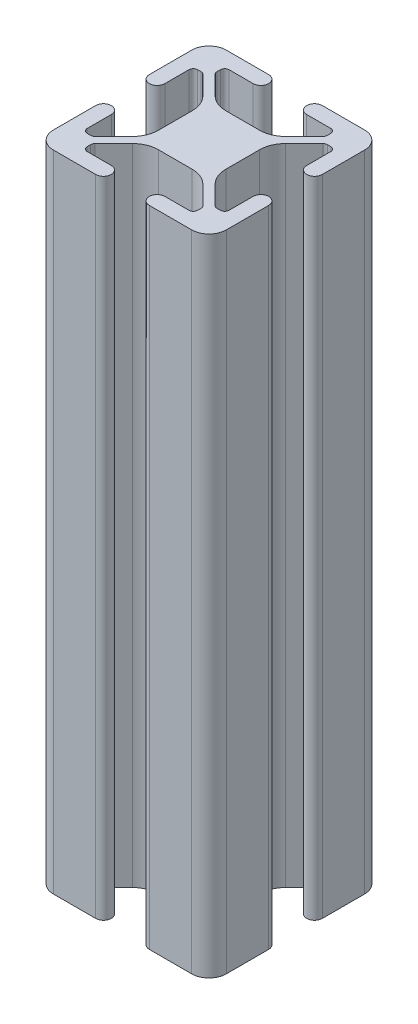
SolidWorks part; units mm, degrees
ref_plane "前视基准面" through (0, 0, 0) normal (0, 0, 1) x (1, 0, 0)
ref_plane "上视基准面" through (0, 0, 0) normal (0, 1, 0) x (1, 0, 0)
ref_plane "右视基准面" through (0, 0, 0) normal (1, 0, 0) x (0, 0, -1)
sketch "草图1" plane through (0, 0, 0) normal (0, 1, 0) x (1, 0, 0)
  line L0 (-1.0428, -10.0859) -> (3.8572, -10.0859)
  line L1 (1.0762, -11.8859) -> (3.8572, -11.8859)
  line L2 (2.8854, -15.3072) -> (0.7226, -13.1443)
  line L3 (2.1786, -16.0141) -> (0.0157, -13.8512)
  line L4 (-3.0428, -12.0859) -> (-3.0428, -16.9859)
  line L5 (-1.2428, -14.2048) -> (-1.2428, -16.9859)
  line L6 (-0.7428, -13.7048) -> (-0.3378, -13.7048)
  line L7 (0.5762, -12.3859) -> (0.5762, -12.7908)
  line L8 (-1.0428, -30.0859) -> (3.8572, -30.0859)
  line L9 (1.0762, -28.2859) -> (3.8572, -28.2859)
  line L10 (2.8854, -24.8645) -> (0.7226, -27.0274)
  line L11 (2.1786, -24.1577) -> (0.0157, -26.3205)
  line L12 (-3.0428, -28.0859) -> (-3.0428, -23.1859)
  line L13 (-1.2428, -25.9669) -> (-1.2428, -23.1859)
  line L14 (-0.7428, -26.4669) -> (-0.3378, -26.4669)
  line L15 (0.5762, -27.7859) -> (0.5762, -27.3809)
  line L16 (14.9572, -10.0859) -> (10.0572, -10.0859)
  line L17 (12.8383, -11.8859) -> (10.0572, -11.8859)
  line L18 (11.029, -15.3072) -> (13.1919, -13.1443)
  line L19 (11.7359, -16.0141) -> (13.8988, -13.8512)
  line L20 (16.9572, -12.0859) -> (16.9572, -16.9859)
  line L21 (15.1572, -14.2048) -> (15.1572, -16.9859)
  line L22 (14.6572, -13.7048) -> (14.2523, -13.7048)
  line L23 (13.3383, -12.3859) -> (13.3383, -12.7908)
  line L24 (14.9572, -30.0859) -> (10.0572, -30.0859)
  line L25 (12.8383, -28.2859) -> (10.0572, -28.2859)
  line L26 (11.029, -24.8645) -> (13.1919, -27.0274)
  line L27 (11.7359, -24.1577) -> (13.8988, -26.3205)
  line L28 (16.9572, -28.0859) -> (16.9572, -23.1859)
  line L29 (15.1572, -25.9669) -> (15.1572, -23.1859)
  line L30 (14.6572, -26.4669) -> (14.2523, -26.4669)
  line L31 (13.3383, -27.7859) -> (13.3383, -27.3809)
  line L32 (5.0068, -16.1859) -> (8.9077, -16.1859)
  line L33 (10.8572, -18.1354) -> (10.8572, -22.0363)
  line L34 (3.0572, -18.1354) -> (3.0572, -22.0363)
  line L35 (5.0068, -23.9859) -> (8.9077, -23.9859)
  circle A0 centre (6.9572, -20.0859) radius 2.5
  arc A1 (2.8854, -15.3072) -> (5.0068, -16.1859) centre (5.0068, -13.1859) ccw
  arc A2 (3.0572, -18.1354) -> (2.1786, -16.0141) centre (0.0572, -18.1354) ccw
  arc A3 (3.8572, -11.8859) -> (3.8572, -10.0859) centre (3.8572, -10.9859) ccw
  arc A4 (0.5762, -12.7908) -> (0.7226, -13.1443) centre (1.0762, -12.7908) ccw
  arc A5 (0.0157, -13.8512) -> (-0.3378, -13.7048) centre (-0.3378, -14.2048) ccw
  arc A6 (-3.0428, -16.9859) -> (-1.2428, -16.9859) centre (-2.1428, -16.9859) ccw
  arc A7 (-1.0428, -10.0859) -> (-3.0428, -12.0859) centre (-1.0428, -12.0859) ccw
  arc A8 (-0.7428, -13.7048) -> (-1.2428, -14.2048) centre (-0.7428, -14.2048) ccw
  arc A9 (1.0762, -11.8859) -> (0.5762, -12.3859) centre (1.0762, -12.3859) ccw
  arc A10 (5.0068, -23.9859) -> (2.8854, -24.8645) centre (5.0068, -26.9859) ccw
  arc A11 (2.1786, -24.1577) -> (3.0572, -22.0363) centre (0.0572, -22.0363) ccw
  arc A12 (3.8572, -30.0859) -> (3.8572, -28.2859) centre (3.8572, -29.1859) ccw
  arc A13 (0.7226, -27.0274) -> (0.5762, -27.3809) centre (1.0762, -27.3809) ccw
  arc A14 (-0.3378, -26.4669) -> (0.0157, -26.3205) centre (-0.3378, -25.9669) ccw
  arc A15 (-1.2428, -23.1859) -> (-3.0428, -23.1859) centre (-2.1428, -23.1859) ccw
  arc A16 (-3.0428, -28.0859) -> (-1.0428, -30.0859) centre (-1.0428, -28.0859) ccw
  arc A17 (-1.2428, -25.9669) -> (-0.7428, -26.4669) centre (-0.7428, -25.9669) ccw
  arc A18 (0.5762, -27.7859) -> (1.0762, -28.2859) centre (1.0762, -27.7859) ccw
  arc A19 (8.9077, -16.1859) -> (11.029, -15.3072) centre (8.9077, -13.1859) ccw
  arc A20 (11.7359, -16.0141) -> (10.8572, -18.1354) centre (13.8572, -18.1354) ccw
  arc A21 (10.0572, -10.0859) -> (10.0572, -11.8859) centre (10.0572, -10.9859) ccw
  arc A22 (13.1919, -13.1443) -> (13.3383, -12.7908) centre (12.8383, -12.7908) ccw
  arc A23 (14.2523, -13.7048) -> (13.8988, -13.8512) centre (14.2523, -14.2048) ccw
  arc A24 (15.1572, -16.9859) -> (16.9572, -16.9859) centre (16.0572, -16.9859) ccw
  arc A25 (16.9572, -12.0859) -> (14.9572, -10.0859) centre (14.9572, -12.0859) ccw
  arc A26 (15.1572, -14.2048) -> (14.6572, -13.7048) centre (14.6572, -14.2048) ccw
  arc A27 (13.3383, -12.3859) -> (12.8383, -11.8859) centre (12.8383, -12.3859) ccw
  arc A28 (11.029, -24.8645) -> (8.9077, -23.9859) centre (8.9077, -26.9859) ccw
  arc A29 (10.8572, -22.0363) -> (11.7359, -24.1577) centre (13.8572, -22.0363) ccw
  arc A30 (10.0572, -28.2859) -> (10.0572, -30.0859) centre (10.0572, -29.1859) ccw
  arc A31 (13.3383, -27.3809) -> (13.1919, -27.0274) centre (12.8383, -27.3809) ccw
  arc A32 (13.8988, -26.3205) -> (14.2523, -26.4669) centre (14.2523, -25.9669) ccw
  arc A33 (16.9572, -23.1859) -> (15.1572, -23.1859) centre (16.0572, -23.1859) ccw
  arc A34 (14.9572, -30.0859) -> (16.9572, -28.0859) centre (14.9572, -28.0859) ccw
  arc A35 (14.6572, -26.4669) -> (15.1572, -25.9669) centre (14.6572, -25.9669) ccw
  arc A36 (12.8383, -28.2859) -> (13.3383, -27.7859) centre (12.8383, -27.7859) ccw
  point P0 (0, 0.001)
  point P1 (0.001, 0.001)
  point P2 (0.001, 0)
extrude "凸台-拉伸1" add sketch "草图1" along normal blind 74.5 contours L5 A6 L4 A7 L0 A3 L1 A9 L7 A4 L2 A1 L32 A19 L18 A22 L23 A27 L17 A21 L16 A25 L20 A24 L21 A26 L22 A23 L19 A20 L33 A29 L27 A32 L30 A35 L29 A33 L28 A34 L24 A30 L25 A36 L31 A31 L26 A28 L35 A10 L10 A13 L15 A18 L9 A12 L8 A16 L12 A15 L13 A17 L14 A14 L11 A11 L34 A2 L3 A5 L6 A8
